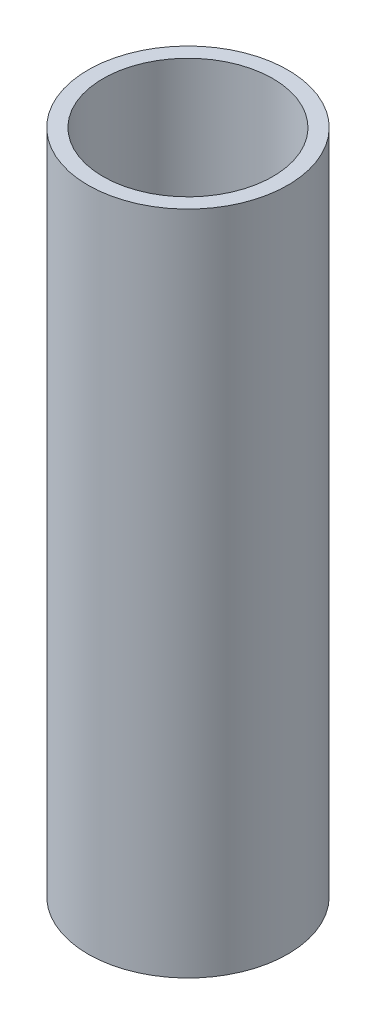
SolidWorks part; units mm, degrees
material "PVC 경질"
ref_plane "정면" through (0, 0, 0) normal (0, 0, 1) x (1, 0, 0)
ref_plane "윗면" through (0, 0, 0) normal (0, 1, 0) x (1, 0, 0)
ref_plane "우측면" through (0, 0, 0) normal (1, 0, 0) x (0, 0, -1)
other "질량 중심(COM)"
sketch "스케치1" plane through (0, 0, 0) normal (0, 1, 0) x (1, 0, 0)
  circle A0 centre (0, 0) radius 30
  circle A1 centre (0, 0) radius 25.5
  dimension "D1" = 60
  dimension "D2" = 51
extrude "보스-돌출1" add sketch "스케치1" along normal blind 200
